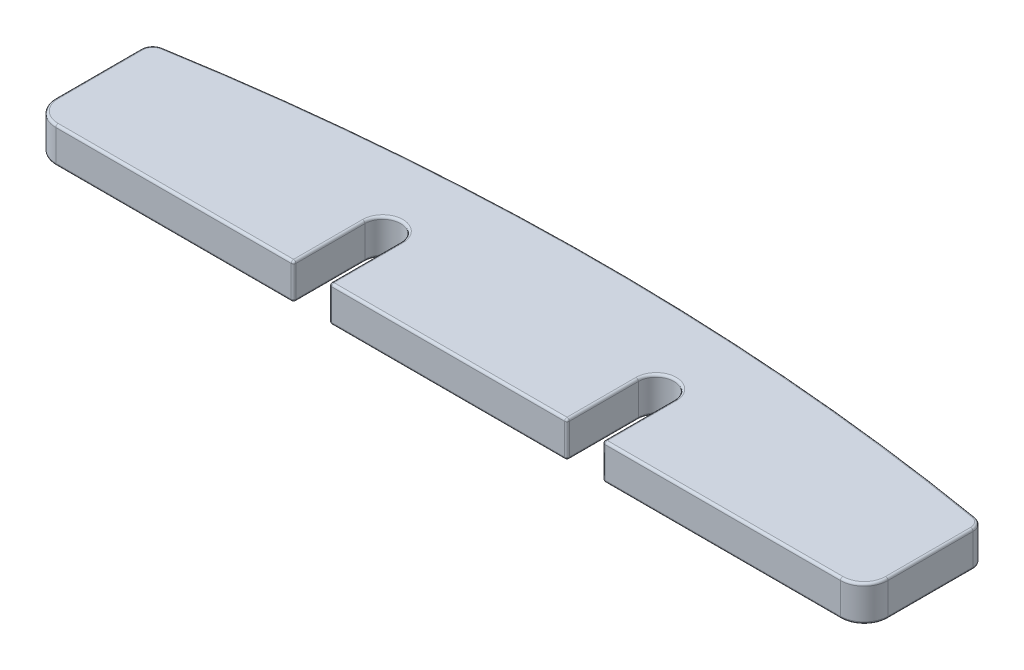
SolidWorks part; units mm, degrees
ref_plane "Front Plane" through (0, 0, 0) normal (0, 0, 1) x (1, 0, 0)
ref_plane "Top Plane" through (0, 0, 0) normal (0, 1, 0) x (1, 0, 0)
ref_plane "Right Plane" through (0, 0, 0) normal (1, 0, 0) x (0, 0, -1)
sketch "Sketch1" plane through (0, 0, 0) normal (0, 1, 0) x (1, 0, 0)
  line L0 (0, 0) -> (0, 13) construction
  line L1 (10, 0) -> (-10, 0)
  line L2 (-10, 0) -> (-10, 6)
  line L3 (35, 2) -> (35, 9.1566)
  line L4 (-13, 6) -> (-13, 0)
  line L5 (-13, 0) -> (-33, 0)
  line L6 (-35, 2) -> (-35, 9.1566)
  line L7 (13, 0) -> (33, 0)
  line L8 (13, 6) -> (13, 0)
  line L9 (10, 0) -> (10, 6)
  arc A0 (-10, 6) -> (-13, 6) centre (-11.5, 6) ccw
  arc A1 (34.1667, 10.1426) -> (-34.1667, 10.1426) centre (0, -191.9901) ccw
  arc A2 (-33, 0) -> (-35, 2) centre (-33, 2) cw
  arc A3 (-35, 9.1566) -> (-34.1667, 10.1426) centre (-34, 9.1566) cw
  arc A4 (35, 9.1566) -> (34.1667, 10.1426) centre (34, 9.1566) ccw
  arc A5 (33, 0) -> (35, 2) centre (33, 2) ccw
  arc A6 (10, 6) -> (13, 6) centre (11.5, 6) cw
  point P13 (-35, 0)
  point P16 (-35, 10)
  point P28 (35, 10)
  point P29 (35, 0)
  dimension "D3" = 6
  dimension "D4" = 35
  dimension "D5" = 13
  dimension "D7" = 2
  dimension "D8" = 1
  dimension "D9" = 205
  dimension "D1" = 10
  dimension "D2" = 3
  dimension "D6" = 10
extrude "Boss-Extrude1" add sketch "Sketch1" along normal blind 3
fillet "Fillet1" radius 0.2 36 edges at (0, 0, 0) (10, 0, -3) (11.5, 0, -7.5) (13, 0, -3) (23, 0, 0) (34.4142, 0, -0.5858) (35, 0, -5.5783) (34.7638, 0, -9.8021) (0, 0, -13.0099) (-34.7638, 0, -9.8021) (-35, 0, -5.5783) (-34.4142, 0, -0.5858) (-23, 0, 0) (-13, 0, -3) (-11.5, 0, -7.5) (-10, 0, -3) (-11.5, 3, -7.5) (-13, 3, -3) (-23, 3, 0) (-34.4142, 3, -0.5858) (-35, 3, -5.5783) (-34.7638, 3, -9.8021) (0, 3, -13.0099) (34.7638, 3, -9.8021) (35, 3, -5.5783) (34.4142, 3, -0.5858) (23, 3, 0) (13, 3, -3) (11.5, 3, -7.5) (10, 3, -3) (0, 3, 0) (-10, 3, -3) (13, 1.5, 0) (10, 1.5, 0) (-10, 1.5, 0) (-13, 1.5, 0)
